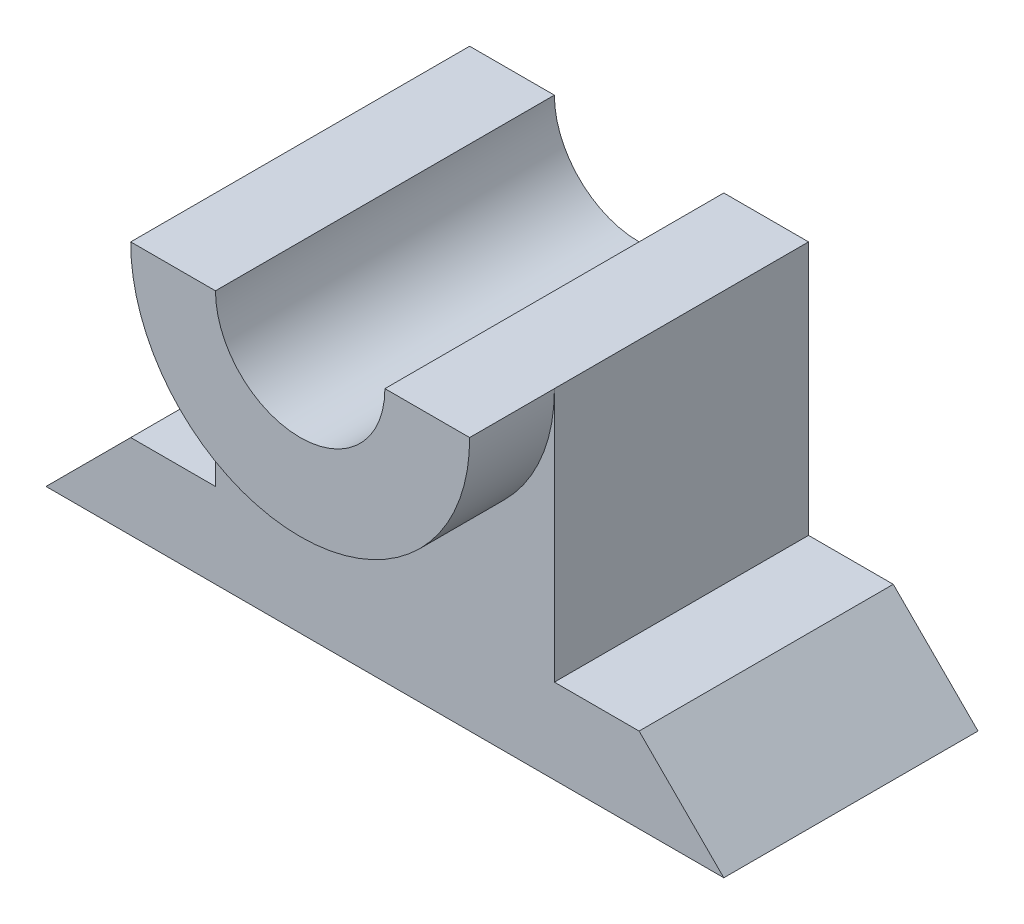
SolidWorks part; units mm, degrees
ref_plane "前基準面" through (0, 0, 0) normal (0, 0, 1) x (1, 0, 0)
ref_plane "上基準面" through (0, 0, 0) normal (0, 1, 0) x (1, 0, 0)
ref_plane "右基準面" through (0, 0, 0) normal (1, 0, 0) x (0, 0, -1)
sketch "草圖1" plane through (0, 0, 0) normal (0, 0, 1) x (1, 0, 0)
  line L0 (-40, 0) -> (40, 0)
  line L1 (40, 0) -> (30, 10)
  line L2 (30, 10) -> (20, 10)
  line L3 (20, 10) -> (20, 40)
  line L4 (20, 40) -> (-20, 40)
  line L6 (0, 0) -> (0, -42.6085) construction
  line L7 (-20, 10) -> (-20, 40)
  line L8 (-30, 10) -> (-20, 10)
  line L9 (-40, 0) -> (-30, 10)
  dimension "D1" = 40
  dimension "D3" = 40
  dimension "D4" = 10
  dimension "D5" = 10
extrude "填料-伸長1" add sketch "草圖1" along normal blind 30
sketch "草圖2" plane through (0, 0, 30) normal (0, 0, 1) x (1, 0, 0)
  line L0 (-20, 40) -> (20, 40)
  arc A0 (-20, 40) -> (20, 40) centre (0, 39.8723) ccw
extrude "填料-伸長2" add sketch "草圖2" along normal blind 10
sketch "草圖3" plane through (0, 0, 40) normal (0, 0, 1) x (1, 0, 0)
  line L0 (20, 40) -> (-20, 40) construction
  line L1 (10, 40) -> (-10, 40)
  arc A0 (-10, 40) -> (10, 40) centre (0, 40) ccw
extrude "除料-伸長1" cut sketch "草圖3" against normal blind 70
